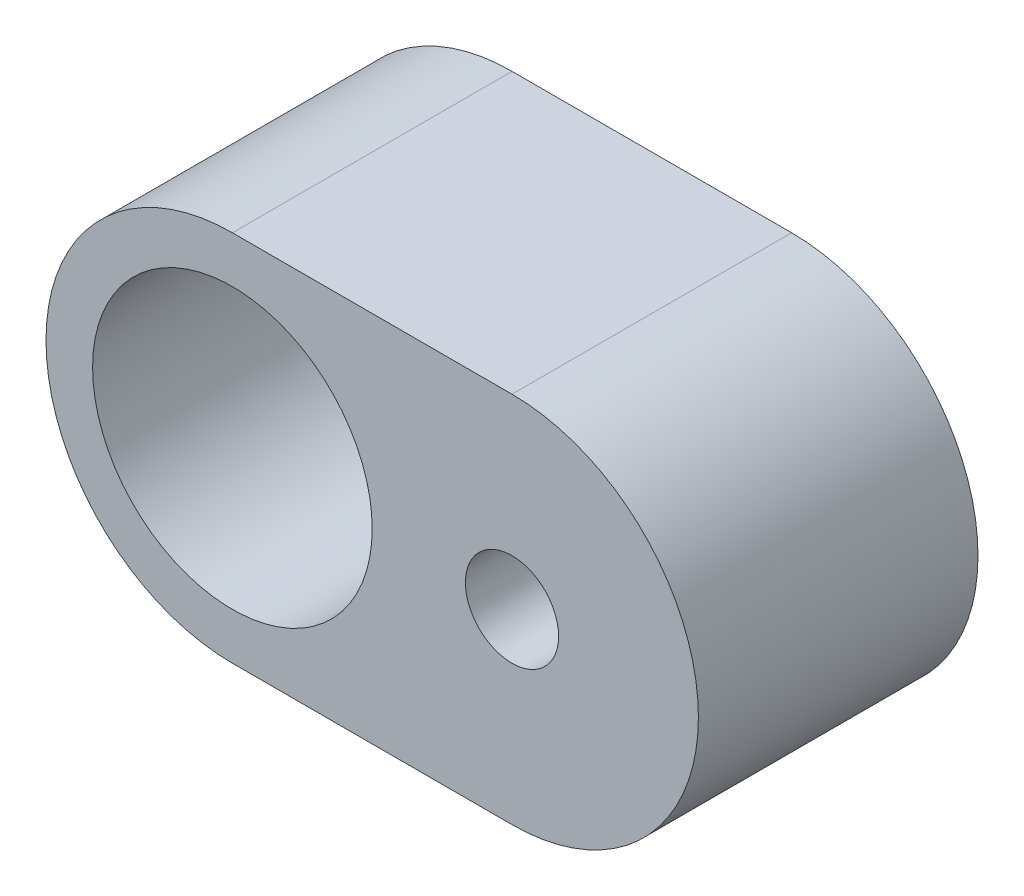
SolidWorks part; units mm, degrees
ref_plane "Front Plane" through (0, 0, 0) normal (0, 0, 1) x (1, 0, 0)
ref_plane "Top Plane" through (0, 0, 0) normal (0, 1, 0) x (1, 0, 0)
ref_plane "Right Plane" through (0, 0, 0) normal (1, 0, 0) x (0, 0, -1)
sketch "Sketch1" plane through (0, 0, 0) normal (0, 0, 1) x (1, 0, 0)
  line L0 (-30, 0) -> (0, 0) construction
  line L1 (-30, 20) -> (0, 20)
  line L2 (-30, -20) -> (0, -20)
  arc A0 (-30, 20) -> (-30, -20) centre (-30, 0) ccw
  arc A1 (0, -20) -> (0, 20) centre (0, 0) ccw
  point P3 (-15, 0)
  dimension "D2" = 20
  dimension "D1" = 30
extrude "Boss-Extrude1" add sketch "Sketch1" along normal blind 30
sketch "Sketch2" plane through (0, 0, 0) normal (0, 0, 1) x (1, 0, 0)
  circle A0 centre (-30, 0) radius 15
  circle A1 centre (0, 0) radius 5
  dimension "D1" = 30
  dimension "D2" = 10
extrude "Cut-Extrude1" cut sketch "Sketch2" along normal through all
